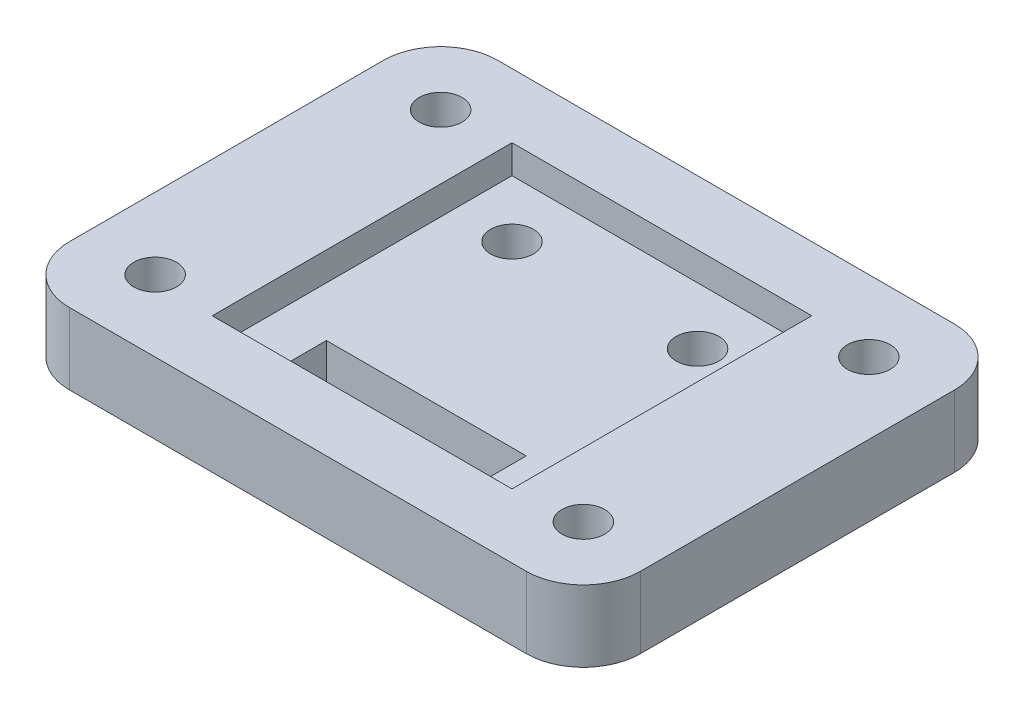
SolidWorks part; units mm, degrees
ref_plane "Front" through (0, 0, 0) normal (0, 0, 1) x (1, 0, 0)
ref_plane "Top" through (0, 0, 0) normal (0, 1, 0) x (1, 0, 0)
ref_plane "Right" through (0, 0, 0) normal (1, 0, 0) x (0, 0, -1)
sketch "Sketch1" plane through (0, 0, 0) normal (0, 1, 0) x (1, 0, 0)
  line L1 (0, 0) -> (40, 0)
  line L2 (0, 0) -> (0, 30)
  line L3 (0, 30) -> (40, 30)
  line L4 (40, 0) -> (40, 30)
  dimension "D1" = 40
  dimension "D2" = 30
extrude "Boss-Extrude1" add sketch "Sketch1" along normal blind 5
sketch "Sketch2" plane through (0, 5, 0) normal (0, 1, 0) x (1, 0, 0)
  line L1 (9.5, 4.5) -> (30.5, 4.5)
  line L2 (9.5, 4.5) -> (9.5, 25.5)
  line L3 (9.5, 25.5) -> (30.5, 25.5)
  line L4 (30.5, 4.5) -> (30.5, 25.5)
  line L5 (0, 0) -> (40, 0) construction
  line L6 (0, 30) -> (0, 0) construction
  point P4 (9.5, 15)
  point P6 (20, 4.5)
  point P9 (20, 0)
  point P11 (0, 15)
  dimension "D1" = 21
  dimension "D2" = 21
extrude "Cut-Extrude1" cut sketch "Sketch2" against normal blind 2
sketch "Sketch3" plane through (0, 3, 0) normal (0, 1, 0) x (1, 0, 0)
  line L0 (9.5, 4.5) -> (30.5, 4.5) construction
  line L1 (13, 6) -> (27, 6)
  line L2 (13, 6) -> (13, 9)
  line L3 (13, 9) -> (27, 9)
  line L4 (27, 6) -> (27, 9)
  point P4 (20, 6)
  point P7 (20, 4.5)
  dimension "D1" = 14
  dimension "D2" = 3
  dimension "D3" = 1.5
extrude "Cut-Extrude2" cut sketch "Sketch3" against normal up to surface (3 mm away) up to face at (20, 0, -15)
sketch "Sketch4" plane through (0, 3, 0) normal (0, 1, 0) x (1, 0, 0)
  line L0 (9.5, 25.5) -> (9.5, 4.5) construction
  line L1 (30.5, 25.5) -> (9.5, 25.5) construction
  line L2 (30.5, 4.5) -> (30.5, 25.5) construction
  circle A0 centre (13.5, 21.5) radius 1.5
  circle A1 centre (26.5, 21.5) radius 1.5
  dimension "D4" = 3
  dimension "D5" = 3
  dimension "D1" = 4
  dimension "D2" = 4
  dimension "D3" = 4
extrude "Cut-Extrude3" cut sketch "Sketch4" against normal up to surface (3 mm away) up to face at (20, 0, -7.5)
sketch "Sketch5" plane through (0, 5, 0) normal (0, 1, 0) x (1, 0, 0)
  line L0 (0, 30) -> (0, 0) construction
  line L1 (0, 0) -> (40, 0) construction
  line L2 (20, 0) -> (20, 30) construction
  line L3 (40, 30) -> (0, 30) construction
  line L4 (0, 15) -> (40, 15) construction
  line L5 (40, 0) -> (40, 30) construction
  circle A0 centre (5, 25) radius 1.5
  circle A1 centre (35, 5) radius 1.5
  circle A2 centre (35, 25) radius 1.5
  circle A3 centre (5, 5) radius 1.5
  dimension "D1" = 3
  dimension "D2" = 5
  dimension "D3" = 5
extrude "Cut-Extrude4" cut sketch "Sketch5" against normal up to surface (5 mm away) up to face at (26.5, 0, -23)
fillet "Fillet1" radius 4 4 edges at (0, 2.5, 0) (40, 2.5, -30) (40, 2.5, 0) (0, 2.5, -30)
